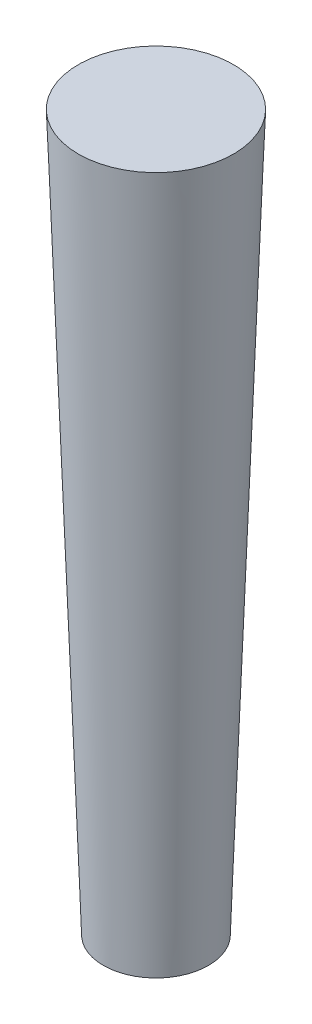
SolidWorks part; units mm, degrees
ref_plane "Front Plane" through (0, 0, 0) normal (0, 0, 1) x (1, 0, 0)
ref_plane "Top Plane" through (0, 0, 0) normal (0, 1, 0) x (1, 0, 0)
ref_plane "Right Plane" through (0, 0, 0) normal (1, 0, 0) x (0, 0, -1)
sketch "Sketch1" plane through (0, 0, 0) normal (0, 1, 0) x (1, 0, 0)
  circle A0 centre (0, 0) radius 2.5
  dimension "D1" = 5
extrude "Boss-Extrude1" add sketch "Sketch1" along normal blind 34 draft 2 draft outward yes
